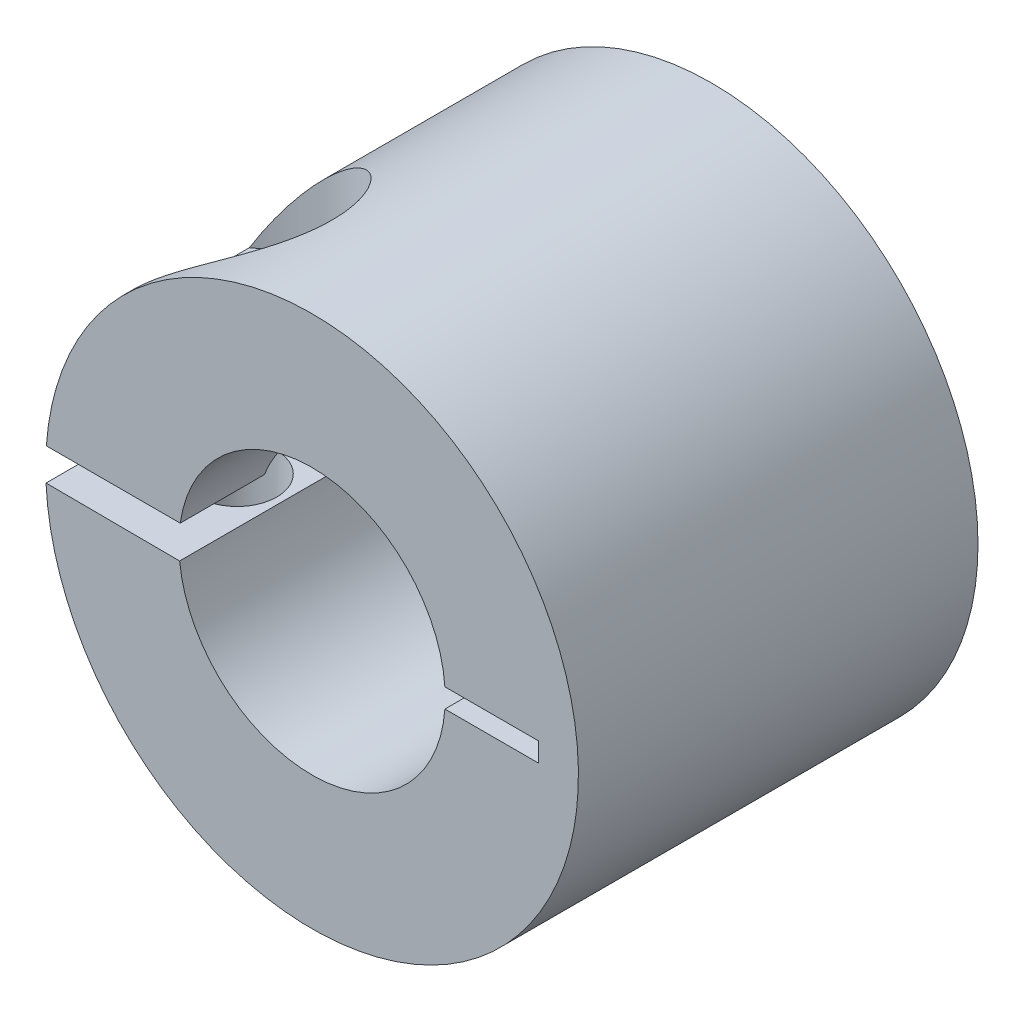
SolidWorks part; units mm, degrees
ref_plane "前视基准面" through (0, 0, 0) normal (0, 0, 1) x (1, 0, 0)
ref_plane "上视基准面" through (0, 0, 0) normal (0, 1, 0) x (1, 0, 0)
ref_plane "右视基准面" through (0, 0, 0) normal (1, 0, 0) x (0, 0, -1)
sketch "草图1" plane through (0, 0, 0) normal (0, 0, 1) x (1, 0, 0)
  line L0 (0, 0) -> (-25.7403, 0) construction
  line L1 (-13.9642, 1) -> (-6.9282, 1)
  line L2 (-13.9825, -0.7) -> (-6.9611, -0.7368)
  arc A0 (-13.9825, -0.7) -> (-13.9642, 1) centre (0, 0) ccw
  arc A1 (-6.9611, -0.7368) -> (-6.9282, 1) centre (0, 0) ccw
  dimension "D1" = 28
  dimension "D2" = 14
  dimension "D3" = 2
extrude "凸台-拉伸1" add sketch "草图1" along normal blind 11
sketch "草图2" plane through (0, 0, 11) normal (0, 0, 1) x (1, 0, 0)
  line L0 (0, 0) -> (24.0374, 0) construction
  line L1 (6.9817, 0.5058) -> (11.8988, 0.5058)
  line L2 (11.8988, 0.5058) -> (11.8988, -0.5058)
  line L3 (6.9817, -0.5058) -> (11.8988, -0.5058)
  circle A0 centre (0, 0) radius 7 construction
  arc A1 (6.9817, -0.5058) -> (6.9817, 0.5058) centre (0, 0) ccw
  point P10 (11.8988, 0)
sketch "草图3" plane through (0, 0, 0) normal (0, 1, 0) x (1, 0, 0)
  line L0 (11.8988, -11) -> (9.4678, -8.569)
  line L1 (6.9817, -11) -> (11.8988, -11) construction
  dimension "D1" = 45
sweep "切除-扫描1" cut profiles "草图2" path "草图3"
ref_plane "基准面1" through (0, 6, 0) normal (0, 1, 0) x (1, 0, 0)
sketch "草图6" plane through (0, 6, 0) normal (0, 1, 0) x (1, 0, 0)
  line L0 (-13.9642, -5.5) -> (-9.4642, -5.5) construction
  line L1 (-13.9642, -11) -> (-13.9642, 0) construction
  circle A0 centre (-9.4642, -5.5) radius 5
  dimension "D1" = 10
  dimension "D2" = 4.5
extrude "切除-拉伸2" cut sketch "草图6" along normal blind 15
sketch "草图7" plane through (0, 6, 0) normal (0, 1, 0) x (1, 0, 0)
  circle A0 centre (-9.4642, -5.5) radius 2.75
  dimension "D1" = 5.5
extrude "切除-拉伸3" cut sketch "草图7" against normal blind 6
sketch "草图8" plane through (0, 0, 0) normal (0, 0, -1) x (-1, 0, 0)
  circle A0 centre (0, 0) radius 7
  circle A1 centre (0, 0) radius 14
  dimension "D1" = 28
sketch "草图11" plane through (0, 0, 0) normal (0, 0, 1) x (1, 0, 0)
  line L0 (6.9817, -0.5058) -> (19.9936, -0.5058)
  line L1 (0, 9.5) -> (0, 20)
  arc A0 (0, 20) -> (19.9936, -0.5058) centre (0, 0) ccw
  circle A1 centre (0, 0) radius 9.5
  dimension "D1" = 19
  dimension "D2" = 40
sketch "草图18" plane through (0, 0, 0) normal (0, 0, -1) x (-1, 0, 0)
  circle A0 centre (0, 0) radius 14
  circle A1 centre (0, 0) radius 7
  dimension "D1" = 14
  dimension "D2" = 28
extrude "凸台-拉伸2" add sketch "草图18" along normal blind 10
hole_wizard "M5 螺纹孔2" positions "草图20" profile "草图19" tap size "M5" standard "Gb"
sketch "草图20" plane through (-0.0041, -0.7733, 0) normal (0.0052, 1, 0) x (1, -0.0052, 0)
  point P0 (-9.411, -5.5403)
sketch "草图19" plane through (-9.415, -0.724, 5.5403) normal (0, 0, 1) x (-1, 0.0052, 0)
  line L0 (0, 0) -> (0, 20.2618)
  line L1 (0, 20.2618) -> (2.1, 19)
  line L2 (2.1, 19) -> (2.1, 0)
  line L5 (2.1, 0) -> (0, 0)
  line L10 (0, 20.2618) -> (-2.1, 19) construction
  line L11 (0, -6.35) -> (0, 107.95) construction
  dimension "螺纹孔钻头直径" = 4.2
  dimension "螺纹孔钻头深度" = 19
  dimension "导头角度" = 118
cosmetic thread "孔螺蚊线4" parameters "D1"=11.166, "D2"=5
